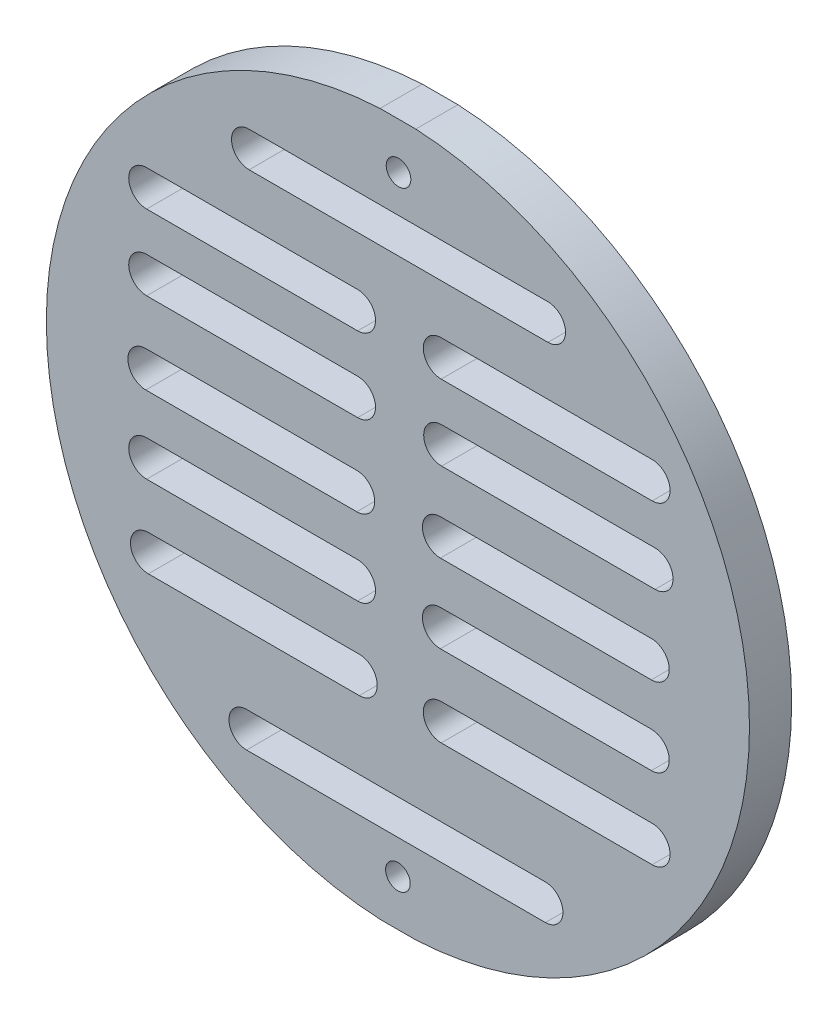
SolidWorks part; units mm, degrees
ref_plane "Alzado" through (0, 0, 0) normal (0, 0, 1) x (1, 0, 0)
ref_plane "Planta" through (0, 0, 0) normal (0, 1, 0) x (1, 0, 0)
ref_plane "Vista lateral" through (0, 0, 0) normal (1, 0, 0) x (0, 0, -1)
sketch "Croquis1" plane through (0, 0, 0) normal (0, 0, 1) x (1, 0, 0)
  line L0 (-42.323, 71.1357) -> (42.677, 71.1357) construction
  line L1 (-42.323, 76.1357) -> (42.677, 76.1357)
  line L2 (-42.323, 66.1357) -> (42.677, 66.1357)
  line L3 (-43.0516, -72.15) -> (41.9484, -72.15) construction
  line L4 (-43.0516, -67.15) -> (41.9484, -67.15)
  line L5 (-43.0516, -77.15) -> (41.9484, -77.15)
  line L6 (12.077, -19.55) -> (72.077, -19.55) construction
  line L9 (12.4342, 25.6214) -> (73.1484, 25.6214) construction
  line L10 (12.4342, 30.7214) -> (73.1484, 30.7214)
  line L11 (12.4342, 20.5214) -> (73.1484, 20.5214)
  line L12 (12.3199, 46.9929) -> (72.3199, 46.9929) construction
  line L13 (12.3199, 52.0929) -> (72.3199, 52.0929)
  line L14 (12.3199, 41.8929) -> (72.3199, 41.8929)
  line L15 (12.3199, -42.6214) -> (72.3199, -42.6214) construction
  line L16 (12.3199, -37.5214) -> (72.3199, -37.5214)
  line L17 (12.3199, -47.7214) -> (72.3199, -47.7214)
  line L18 (12.077, 2.7929) -> (72.077, 2.7929) construction
  line L19 (12.077, 7.8929) -> (72.077, 7.8929)
  line L20 (12.077, -2.3071) -> (72.077, -2.3071)
  line L21 (-71.4658, 46.9929) -> (-11.4658, 46.9929) construction
  line L22 (-71.4658, 52.0929) -> (-11.4658, 52.0929)
  line L23 (-71.4658, 41.8929) -> (-11.4658, 41.8929)
  line L24 (-71.4658, 25.6214) -> (-11.4658, 25.6214) construction
  line L25 (-71.4658, 30.7214) -> (-11.4658, 30.7214)
  line L26 (-71.4658, 20.5214) -> (-11.4658, 20.5214)
  line L27 (-71.7087, 2.3071) -> (-11.7087, 2.3071) construction
  line L28 (-71.7087, 7.4071) -> (-11.7087, 7.4071)
  line L29 (-71.7087, -2.7929) -> (-11.7087, -2.7929)
  line L30 (-71.4658, -19.55) -> (-11.4658, -19.55) construction
  line L31 (-71.4658, -14.45) -> (-11.4658, -14.45)
  line L32 (-71.4658, -24.65) -> (-11.4658, -24.65)
  line L33 (-70.9801, -42.6214) -> (-10.9801, -42.6214) construction
  line L34 (-70.9801, -37.5214) -> (-10.9801, -37.5214)
  line L35 (-70.9801, -47.7214) -> (-10.9801, -47.7214)
  line L36 (12.077, -14.45) -> (72.077, -14.45)
  line L37 (-5.0803, -99.8709) -> (5.0803, -99.8709)
  line L39 (-5.0803, 99.8709) -> (5.0803, 99.8709)
  line L43 (12.077, -24.65) -> (72.077, -24.65)
  circle A0 centre (0, 0) radius 100
  arc A1 (-42.323, 76.1357) -> (-42.323, 66.1357) centre (-42.323, 71.1357) ccw
  arc A2 (42.677, 66.1357) -> (42.677, 76.1357) centre (42.677, 71.1357) ccw
  arc A3 (-43.0516, -67.15) -> (-43.0516, -77.15) centre (-43.0516, -72.15) ccw
  arc A4 (41.9484, -77.15) -> (41.9484, -67.15) centre (41.9484, -72.15) ccw
  arc A7 (12.4342, 30.7214) -> (12.4342, 20.5214) centre (12.4342, 25.6214) ccw
  arc A8 (73.1484, 20.5214) -> (73.1484, 30.7214) centre (73.1484, 25.6214) ccw
  arc A9 (12.3199, 52.0929) -> (12.3199, 41.8929) centre (12.3199, 46.9929) ccw
  arc A10 (72.3199, 41.8929) -> (72.3199, 52.0929) centre (72.3199, 46.9929) ccw
  arc A11 (12.3199, -37.5214) -> (12.3199, -47.7214) centre (12.3199, -42.6214) ccw
  arc A12 (72.3199, -47.7214) -> (72.3199, -37.5214) centre (72.3199, -42.6214) ccw
  arc A13 (12.077, 7.8929) -> (12.077, -2.3071) centre (12.077, 2.7929) ccw
  arc A14 (72.077, -2.3071) -> (72.077, 7.8929) centre (72.077, 2.7929) ccw
  arc A15 (-71.4658, 52.0929) -> (-71.4658, 41.8929) centre (-71.4658, 46.9929) ccw
  arc A16 (-11.4658, 41.8929) -> (-11.4658, 52.0929) centre (-11.4658, 46.9929) ccw
  arc A17 (-71.4658, 30.7214) -> (-71.4658, 20.5214) centre (-71.4658, 25.6214) ccw
  arc A18 (-11.4658, 20.5214) -> (-11.4658, 30.7214) centre (-11.4658, 25.6214) ccw
  arc A19 (-71.7087, 7.4071) -> (-71.7087, -2.7929) centre (-71.7087, 2.3071) ccw
  arc A20 (-11.7087, -2.7929) -> (-11.7087, 7.4071) centre (-11.7087, 2.3071) ccw
  arc A21 (-71.4658, -14.45) -> (-71.4658, -24.65) centre (-71.4658, -19.55) ccw
  arc A22 (-11.4658, -24.65) -> (-11.4658, -14.45) centre (-11.4658, -19.55) ccw
  arc A23 (-70.9801, -37.5214) -> (-70.9801, -47.7214) centre (-70.9801, -42.6214) ccw
  arc A24 (-10.9801, -47.7214) -> (-10.9801, -37.5214) centre (-10.9801, -42.6214) ccw
  arc A25 (12.077, -14.45) -> (12.077, -24.65) centre (12.077, -19.55) ccw
  arc A26 (72.077, -24.65) -> (72.077, -14.45) centre (72.077, -19.55) ccw
  circle A27 centre (0.177, 86.7214) radius 3.5
  circle A28 centre (0, -86.8214) radius 3.5
  point P5 (0.177, 71.1357)
  point P11 (-0.5516, -72.15)
  point P19 (42.077, -19.55)
  point P25 (42.7913, 25.6214)
  point P32 (42.3199, 46.9929)
  point P40 (42.3199, -42.6214)
  point P45 (42.077, 2.7929)
  point P52 (-41.4658, 46.9929)
  point P59 (-41.4658, 25.6214)
  point P66 (-41.7087, 2.3071)
  point P73 (-41.4658, -19.55)
  point P80 (-40.9801, -42.6214)
extrude "Saliente-Extruir1" add sketch "Croquis1" along normal blind 2 and the other way blind 10 contours L14 A10 L13 A9 | L11 A8 L10 A7 | L43 A26 L36 A25 | L5 A4 L4 A3 | A28 | L39 A0 L37 A28 A27 A26 L43 A25 L36 A24 L35 A23 L34 A22 L32 A21 L31 A20 L29 A19 L28 A18 L26 A17 L25 A16 L23 A15 L22 A14 L20 A13 L19 A12 L17 A11 L16 A10 L14 | L2 A2 L1 A1
